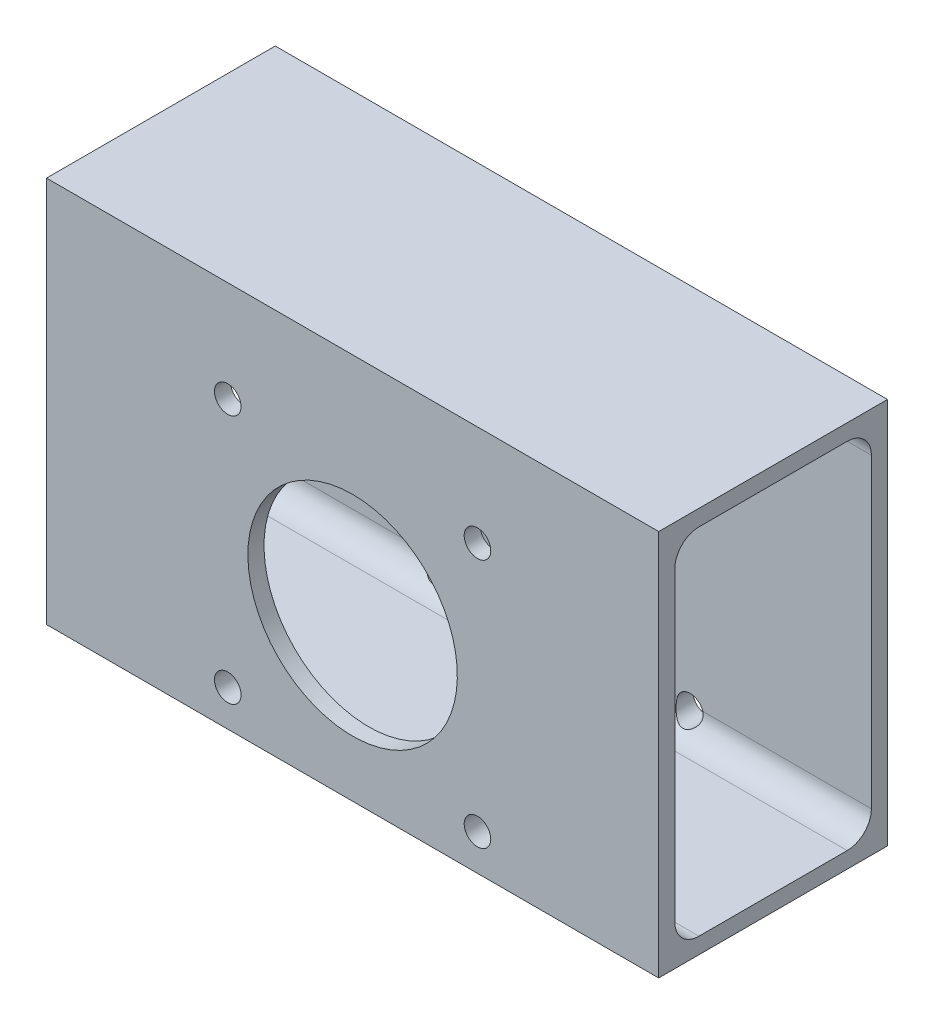
SolidWorks part; units mm, degrees
ref_plane "Front Plane" through (0, 0, 0) normal (0, 0, 1) x (1, 0, 0)
ref_plane "Top Plane" through (0, 0, 0) normal (0, 1, 0) x (1, 0, 0)
ref_plane "Right Plane" through (0, 0, 0) normal (1, 0, 0) x (0, 0, -1)
sketch "ｽｹｯﾁ1" plane through (0, 0, 0) normal (0, 0, 1) x (1, 0, 0)
  line L6 (-38, 0) -> (38, 0)
  line L8 (-38, 0) -> (-38, -48)
  line L9 (-38, -48) -> (38, -48)
  line L10 (38, 0) -> (38, -48)
  circle A0 centre (0, -28) radius 13
  circle A1 centre (-15.5, -43.5) radius 1.65 construction
  circle A2 centre (15.5, -43.5) radius 1.65 construction
  circle A3 centre (-15.5, -12.5) radius 1.65 construction
  circle A4 centre (15.5, -12.5) radius 1.65 construction
  circle A5 centre (-15.5, -43.5) radius 1.65
  circle A6 centre (15.5, -43.5) radius 1.65
  circle A7 centre (-15.5, -12.5) radius 1.65
  circle A8 centre (15.5, -12.5) radius 1.65
  point P0 (0, -28)
  dimension "D1" = 26
extrude "ﾎﾞｽ - 押し出し1" add sketch "ｽｹｯﾁ1" along normal up to surface (28.4 mm away)
sketch "ｽｹｯﾁ2" plane through (0, -48, 0) normal (0, -1, 0) x (1, 0, 0)
  line L0 (-38, 11.6214) -> (38, 11.6214) construction
  line L1 (-38, 28.4) -> (-38, 0) construction
  line L2 (38, 28.4) -> (38, 0) construction
  text T0 "野ウサギ v0.0" font "Meiryo" height in points 20
extrude "ﾎﾞｽ - 押し出し3" add sketch "ｽｹｯﾁ2" along normal blind 1
sketch "ｽｹｯﾁ3" plane through (-38, 0, 0) normal (-1, 0, 0) x (0, 0, 1)
  line L8 (2, -46) -> (26.4, -46)
  line L9 (26.4, -46) -> (26.4, -2)
  line L10 (26.4, -2) -> (2, -2)
  line L11 (2, -2) -> (2, -46)
  line L12 (5, -46) -> (23.4, -46)
  line L13 (26.4, -43) -> (26.4, -5)
  line L14 (23.4, -2) -> (5, -2)
  line L15 (2, -5) -> (2, -43)
  arc A0 (5, -46) -> (2, -43) centre (5, -43) cw
  arc A1 (23.4, -46) -> (26.4, -43) centre (23.4, -43) ccw
  arc A2 (26.4, -5) -> (23.4, -2) centre (23.4, -5) ccw
  arc A3 (5, -2) -> (2, -5) centre (5, -5) ccw
  dimension "D2" = 3
  dimension "D1" = 2
extrude "ｶｯﾄ - 押し出し1" cut sketch "ｽｹｯﾁ3" against normal through all
